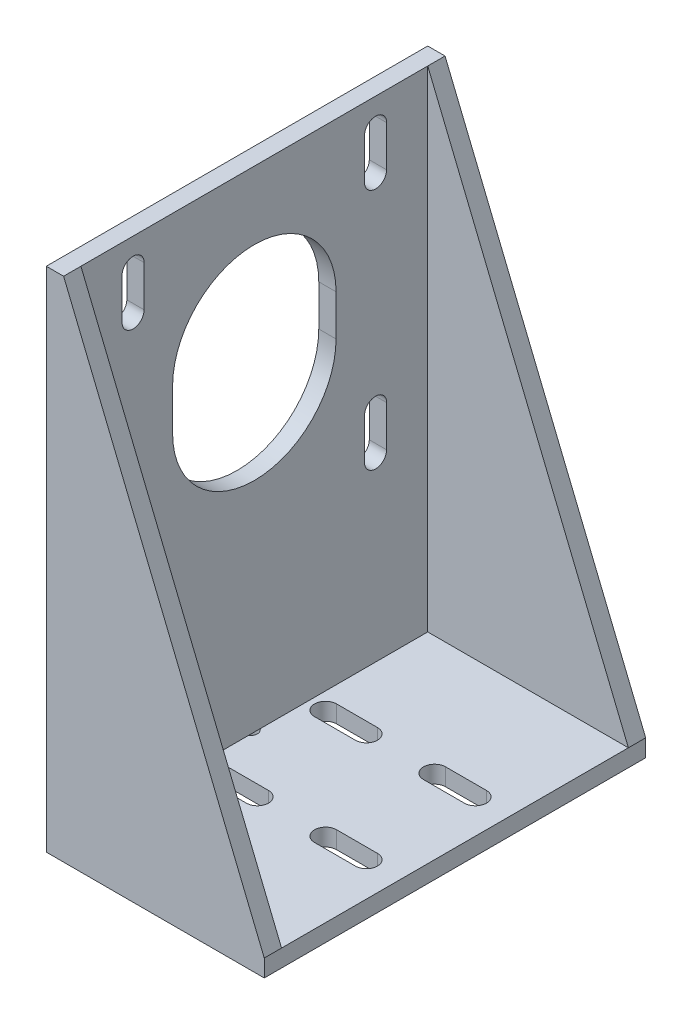
SolidWorks part; units mm, degrees
ref_plane "Front Plane" through (0, 0, 0) normal (0, 0, 1) x (1, 0, 0)
ref_plane "Top Plane" through (0, 0, 0) normal (0, 1, 0) x (1, 0, 0)
ref_plane "Right Plane" through (0, 0, 0) normal (1, 0, 0) x (0, 0, -1)
sketch "Sketch1" plane through (0, 0, 0) normal (0, 1, 0) x (1, 0, 0)
  line L0 (0, 0) -> (80, 0) construction
  line L5 (0, 70) -> (80, 70)
  line L6 (0, 70) -> (0, -70)
  line L7 (0, -70) -> (80, -70)
  line L8 (80, 70) -> (80, -70)
  line L9 (0, 70) -> (80, -70) construction
  line L10 (0, -70) -> (80, 70) construction
  line L11 (12.5, 20) -> (27.5, 20) construction
  line L12 (60, -20) -> (20, -20) construction
  line L13 (60, -20) -> (60, 20) construction
  line L14 (60, 20) -> (20, 20) construction
  line L15 (20, -20) -> (20, 20) construction
  line L16 (60, -20) -> (20, 20) construction
  line L17 (60, 20) -> (20, -20) construction
  line L18 (12.5, 24.05) -> (27.5, 24.05)
  line L19 (12.5, 15.95) -> (27.5, 15.95)
  line L20 (52.5, 20) -> (67.5, 20) construction
  line L21 (52.5, 24.05) -> (67.5, 24.05)
  line L22 (52.5, 15.95) -> (67.5, 15.95)
  line L23 (52.5, -20) -> (67.5, -20) construction
  line L24 (52.5, -15.95) -> (67.5, -15.95)
  line L25 (52.5, -24.05) -> (67.5, -24.05)
  line L26 (12.5, -20) -> (27.5, -20) construction
  line L27 (12.5, -15.95) -> (27.5, -15.95)
  line L28 (12.5, -24.05) -> (27.5, -24.05)
  arc A0 (12.5, 24.05) -> (12.5, 15.95) centre (12.5, 20) ccw
  arc A1 (27.5, 15.95) -> (27.5, 24.05) centre (27.5, 20) ccw
  arc A2 (52.5, 24.05) -> (52.5, 15.95) centre (52.5, 20) ccw
  arc A3 (67.5, 15.95) -> (67.5, 24.05) centre (67.5, 20) ccw
  arc A4 (52.5, -15.95) -> (52.5, -24.05) centre (52.5, -20) ccw
  arc A5 (67.5, -24.05) -> (67.5, -15.95) centre (67.5, -20) ccw
  arc A6 (12.5, -15.95) -> (12.5, -24.05) centre (12.5, -20) ccw
  arc A7 (27.5, -24.05) -> (27.5, -15.95) centre (27.5, -20) ccw
  circle A8 centre (5, 0) radius 2.5
  point P0 (40, 0)
  point P7 (40, 0)
  point P15 (20, 20)
  point P22 (60, 20)
  point P29 (60, -20)
  point P35 (20, -20)
  dimension "D9" = 5
  dimension "D1" = 140
  dimension "D2" = 80
  dimension "D3" = 40
  dimension "D4" = 40
  dimension "D5" = 15
  dimension "D6" = 8.1
  dimension "D7" = 40
  dimension "D8" = 5
extrude "Boss-Extrude1" add sketch "Sketch1" against normal blind 6.35
sketch "Sketch3" plane through (0, 0, 0) normal (1, 0, 0) x (0, 0, -1)
  line L0 (0, 124.95) -> (0, 0) construction
  line L1 (-44.5, 169.45) -> (44.5, 169.45) construction
  line L2 (-44.5, 169.45) -> (-44.5, 80.45) construction
  line L3 (-44.5, 80.45) -> (44.5, 80.45) construction
  line L4 (44.5, 169.45) -> (44.5, 80.45) construction
  line L5 (-44.5, 169.45) -> (44.5, 80.45) construction
  line L6 (-44.5, 80.45) -> (44.5, 169.45) construction
  line L7 (-70, 0) -> (70, 0)
  line L8 (-54.95, 179.9) -> (54.95, 179.9) construction
  line L9 (-54.95, 179.9) -> (-54.95, 70) construction
  line L10 (-54.95, 70) -> (54.95, 70) construction
  line L11 (54.95, 179.9) -> (54.95, 70) construction
  line L12 (-54.95, 179.9) -> (54.95, 70) construction
  line L13 (-54.95, 70) -> (54.95, 179.9) construction
  line L14 (70, 0) -> (70, 179.9)
  line L15 (70, 179.9) -> (-70, 179.9)
  line L16 (-70, 179.9) -> (-70, 0)
  line L17 (-44.5, 169.45) -> (-44.5, 154.45) construction
  line L18 (-40.45, 169.45) -> (-40.45, 154.45)
  line L19 (-48.55, 169.45) -> (-48.55, 154.45)
  line L20 (44.5, 169.45) -> (44.5, 154.45) construction
  line L21 (48.55, 169.45) -> (48.55, 154.45)
  line L22 (40.45, 169.45) -> (40.45, 154.45)
  line L23 (44.5, 80.45) -> (44.5, 65.45) construction
  line L24 (48.55, 80.45) -> (48.55, 65.45)
  line L25 (40.45, 80.45) -> (40.45, 65.45)
  line L26 (-44.5, 80.45) -> (-44.5, 65.45) construction
  line L27 (-40.45, 80.45) -> (-40.45, 65.45)
  line L28 (-48.55, 80.45) -> (-48.55, 65.45)
  line L29 (0, 124.95) -> (0, 109.95) construction
  line L30 (30, 124.95) -> (30, 109.95)
  line L31 (-30, 124.95) -> (-30, 109.95)
  circle A0 centre (-44.5, 169.45) radius 4.05 construction
  circle A1 centre (-44.5, 80.45) radius 4.05 construction
  circle A2 centre (44.5, 80.45) radius 4.05 construction
  circle A3 centre (44.5, 169.45) radius 4.05 construction
  arc A4 (-40.45, 169.45) -> (-48.55, 169.45) centre (-44.5, 169.45) ccw
  arc A5 (-48.55, 154.45) -> (-40.45, 154.45) centre (-44.5, 154.45) ccw
  arc A6 (48.55, 169.45) -> (40.45, 169.45) centre (44.5, 169.45) ccw
  arc A7 (40.45, 154.45) -> (48.55, 154.45) centre (44.5, 154.45) ccw
  arc A8 (48.55, 80.45) -> (40.45, 80.45) centre (44.5, 80.45) ccw
  arc A9 (40.45, 65.45) -> (48.55, 65.45) centre (44.5, 65.45) ccw
  arc A10 (-40.45, 80.45) -> (-48.55, 80.45) centre (-44.5, 80.45) ccw
  arc A11 (-48.55, 65.45) -> (-40.45, 65.45) centre (-44.5, 65.45) ccw
  arc A12 (30, 124.95) -> (-30, 124.95) centre (0, 124.95) ccw
  arc A13 (-30, 109.95) -> (30, 109.95) centre (0, 109.95) ccw
  point P0 (0, 124.95)
  point P22 (-44.5, 161.95)
  point P28 (44.5, 161.95)
  point P34 (44.5, 72.95)
  point P40 (-44.5, 72.95)
  point P46 (0, 117.45)
  dimension "D2" = 8.1
  dimension "D1" = 89
  dimension "D3" = 109.9
  dimension "D4" = 70
  dimension "D5" = 179.9
  dimension "D6" = 8.1
  dimension "D7" = 15
  dimension "D8" = 15
  dimension "D9" = 60
extrude "Boss-Extrude2" add sketch "Sketch3" along normal blind 6.35
sketch "Sketch4" plane through (0, 0, 0) normal (0, 0, 1) x (1, 0, 0)
  line L0 (6.35, 179.9) -> (80, 0)
  line L1 (80, 0) -> (6.35, 0)
  line L2 (6.35, 0) -> (6.35, 179.9)
extrude "Boss-Extrude3" add sketch "Sketch4" along normal blind 70 and the other way blind 70
sketch "Sketch5" plane through (0, 0, 0) normal (0, 0, 1) x (1, 0, 0)
  line L0 (6.35, 179.9) -> (80, 0)
  line L1 (80, 0) -> (6.35, 0)
  line L2 (6.35, 0) -> (6.35, 179.9)
extrude "Cut-Extrude1" cut sketch "Sketch5" against normal blind 63.65 and the other way blind 63.65
